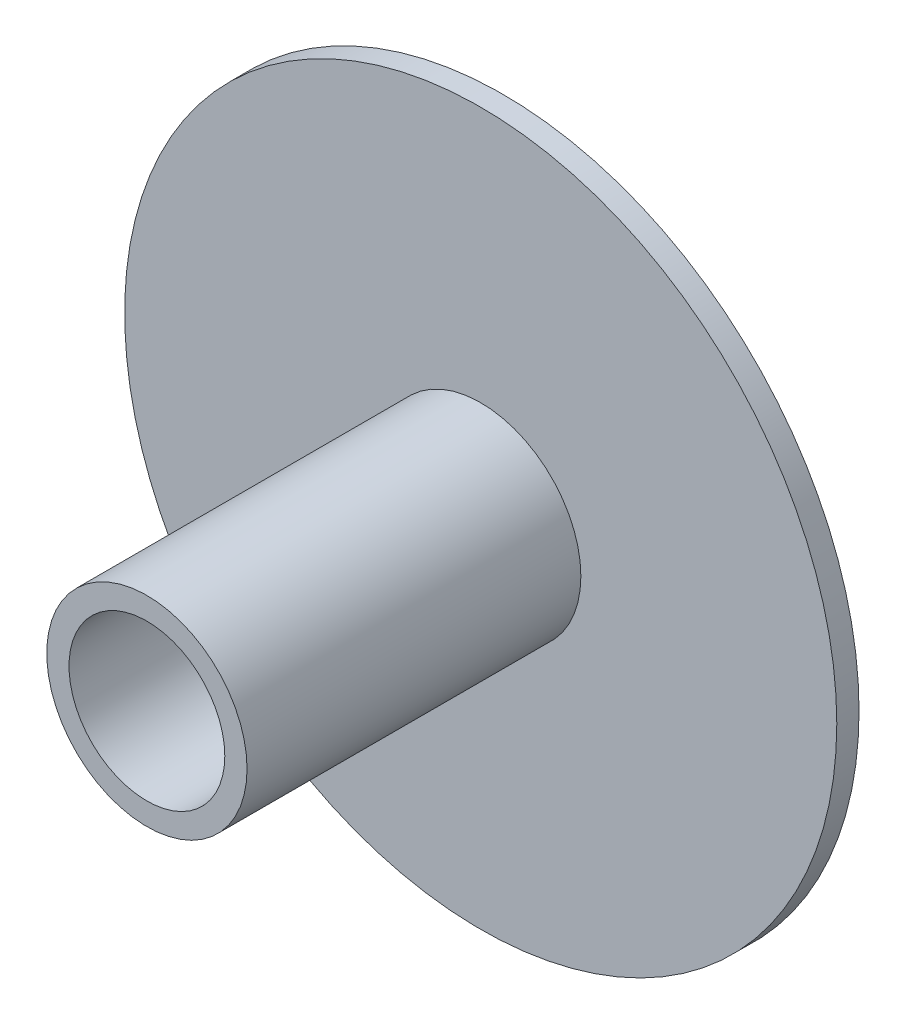
SolidWorks part; units mm, degrees
ref_plane "Front" through (0, 0, 0) normal (0, 0, 1) x (1, 0, 0)
ref_plane "Top" through (0, 0, 0) normal (0, 1, 0) x (1, 0, 0)
ref_plane "Right" through (0, 0, 0) normal (1, 0, 0) x (0, 0, -1)
sketch "Sketch1" plane through (0, 0, 0) normal (0, 0, 1) x (1, 0, 0)
  circle A0 centre (0, 0) radius 15 construction
  circle A1 centre (0, 0) radius 16
  dimension "D1" = 30
  dimension "D2" = 1
extrude "Boss-Extrude1" add sketch "Sketch1" along normal blind 1 contours A1
sketch "Sketch2" plane through (0, 0, 1) normal (0, 0, 1) x (1, 0, 0)
  circle A0 centre (0, 0) radius 3.5 construction
  circle A1 centre (0, 0) radius 4.5
  dimension "D2" = 1
  dimension "D1" = 7
extrude "Boss-Extrude2" add sketch "Sketch2" along normal blind 15
sketch "Sketch3" plane through (0, 0, 16) normal (0, 0, 1) x (1, 0, 0)
  circle A0 centre (0, 0) radius 3.5
  dimension "D1" = 7
extrude "Cut-Extrude1" cut sketch "Sketch3" against normal through all both and the other way through all contours A0
equation "\"D1@Sketch1\"=\"Cavity_Diameter\""
equation "\"Wall_Thickness\"= 1"
equation "\"Cavity_Diameter\"=30"
equation "\"D2@Sketch1\"=\"Wall_Thickness\""
equation "\"D1@Boss-Extrude1\"=\"Wall_Thickness\""
equation "\"Outlet_Diameter\"= 7"
equation "\"D1@Sketch2\"=\"Outlet_Diameter\""
equation "\"Outlet_Length\"= 15"
equation "\"D1@Boss-Extrude2\"=\"Outlet_Length\""
equation "\"D1@Sketch3\"=\"Outlet_Diameter\""
